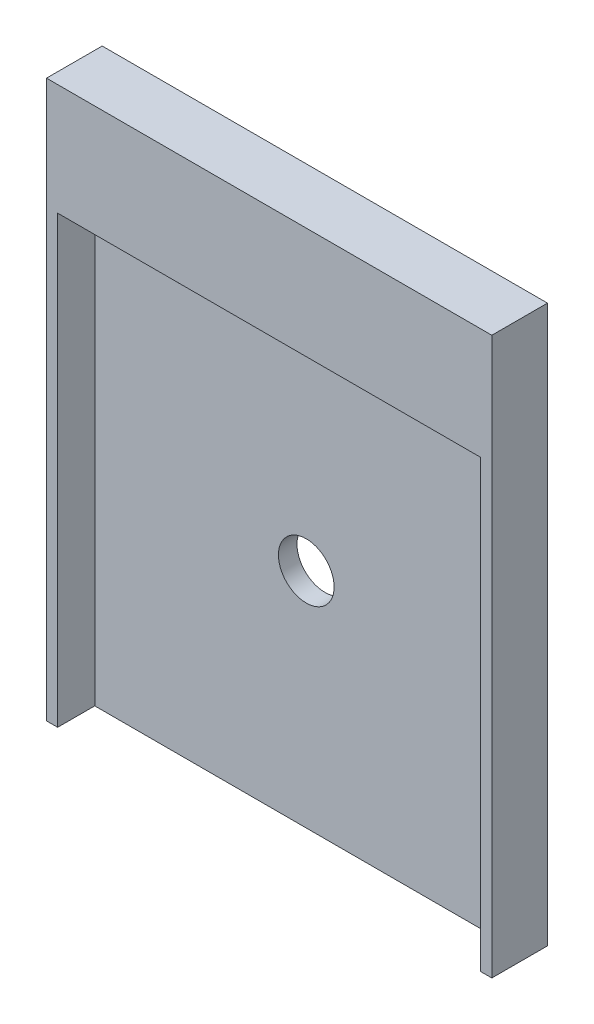
SolidWorks part; units mm, degrees
ref_plane "Front Plane" through (0, 0, 0) normal (0, 0, 1) x (1, 0, 0)
ref_plane "Top Plane" through (0, 0, 0) normal (0, 1, 0) x (1, 0, 0)
ref_plane "Right Plane" through (0, 0, 0) normal (1, 0, 0) x (0, 0, -1)
sketch "Sketch1" plane through (0, 0, 0) normal (0, 0, 1) x (1, 0, 0)
  line L1 (-60, 75) -> (60, 75)
  line L2 (-60, 75) -> (-60, -75)
  line L3 (-60, -75) -> (60, -75)
  line L4 (60, 75) -> (60, -75)
  line L5 (-60, 75) -> (60, -75) construction
  line L6 (-60, -75) -> (60, 75) construction
  point P0 (0, 0)
  dimension "D1" = 120
  dimension "D2" = 150
extrude "Boss-Extrude1" add sketch "Sketch1" along normal blind 5
sketch "Sketch3" plane through (0, 0, 5) normal (0, 0, 1) x (1, 0, 0)
  line L1 (-60, 75) -> (-60, -75) construction
  line L3 (-60, 45) -> (-60, -75)
  line L4 (-60, -75) -> (-57, -75)
  line L6 (-57, 45) -> (-57, -75)
  line L7 (-60, -75) -> (60, -75) construction
  line L8 (60, -75) -> (60, 75) construction
  line L10 (60, 45) -> (60, -75)
  line L11 (60, -75) -> (57, -75)
  line L12 (57, 45) -> (57, -75)
  line L14 (-60, 75) -> (60, 75)
  line L15 (-60, 75) -> (-60, 45)
  line L16 (-57, 45) -> (57, 45)
  line L17 (60, 75) -> (60, 45)
  point P17 (-129.0754, 101.7052)
  dimension "D1" = 3
  dimension "D2" = 3
  dimension "D4" = 120
extrude "Boss-Extrude2" add sketch "Sketch3" along normal blind 10
sketch "Sketch4" plane through (0, 0, 0) normal (0, 0, -1) x (-1, 0, 0)
  line L0 (-60, 75) -> (60, 75) construction
  circle A0 centre (0, -15) radius 7.5
  dimension "D1" = 15
  dimension "D2" = 90
extrude "Cut-Extrude1" cut sketch "Sketch4" against normal blind 10
